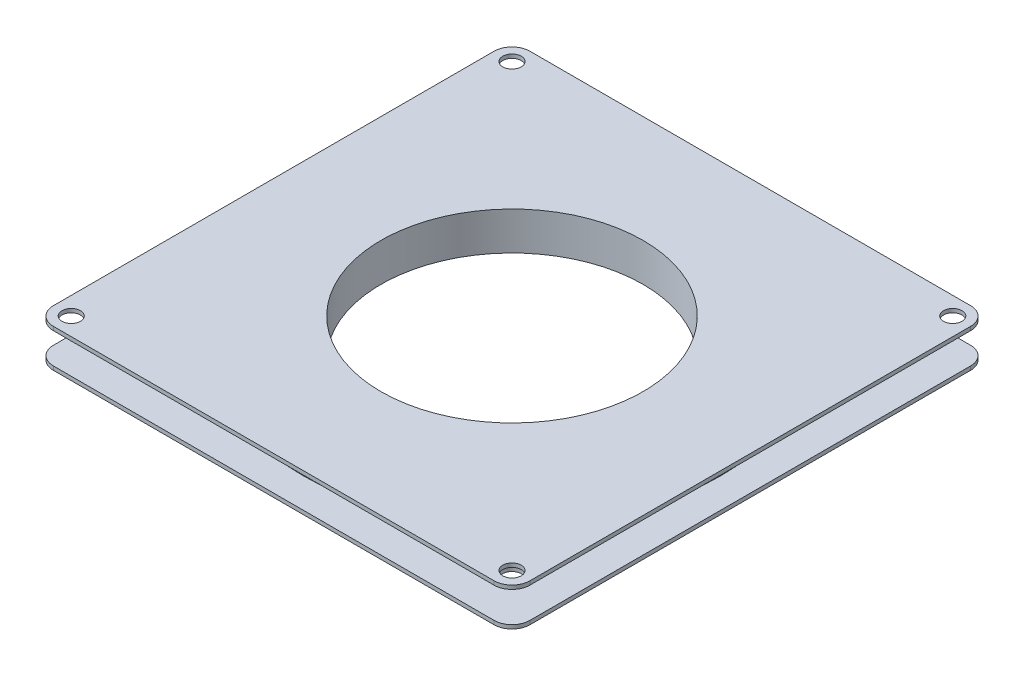
SolidWorks part; units mm, degrees
ref_plane "Front Plane" through (0, 0, 0) normal (0, 0, 1) x (1, 0, 0)
ref_plane "Top Plane" through (0, 0, 0) normal (0, 1, 0) x (1, 0, 0)
ref_plane "Right Plane" through (0, 0, 0) normal (1, 0, 0) x (0, 0, -1)
sketch "Lower_Deck" plane through (0, 0, 0) normal (0, 1, 0) x (1, 0, 0)
  line L1 (0, 0) -> (101.6, 0)
  line L2 (0, 0) -> (0, 101.6)
  line L3 (0, 101.6) -> (101.6, 101.6)
  line L4 (101.6, 0) -> (101.6, 101.6)
  circle A0 centre (10.3505, 10.3505) radius 1.9685
  circle A1 centre (10.3505, 91.2495) radius 1.9685
  circle A2 centre (91.2495, 10.3505) radius 1.9685
  circle A3 centre (91.2495, 91.2495) radius 1.9685
  circle A4 centre (50.8, 50.8) radius 27.94
  point P17 (-50.8076, 117.2435)
  dimension "D1" = 10.3505
  dimension "D7" = 50.8
  dimension "D9" = 55.88
  dimension "D10" = 3.937
  dimension "D2" = 91.2495
  dimension "D3" = 101.6
  dimension "D4" = 101.6
  dimension "D5" = 10.3505
  dimension "D6" = 91.2495
  dimension "D8" = 50.8
extrude "Boss-Extrude1" add sketch "Lower_Deck" along normal blind 0.8128
fillet "Fillet1" radius 3.81 4 edges at (101.6, 0.4064, 0) (101.6, 0.4064, -101.6) (0, 0.4064, -101.6) (0, 0.4064, 0)
ref_plane "Plane1" through (0, 7.3152, 0) normal (0, 1, 0) x (1, 0, 0)
sketch "Sketch2" plane through (0, 7.3152, 0) normal (0, 1, 0) x (1, 0, 0)
  line L1 (0, 0) -> (101.6, 0)
  line L2 (0, 0) -> (0, 101.6)
  line L3 (0, 101.6) -> (101.6, 101.6)
  line L4 (101.6, 0) -> (101.6, 101.6)
  circle A0 centre (50.8, 50.8) radius 27.94
  circle A1 centre (3.81, 3.81) radius 1.9685
  circle A2 centre (3.81, 97.79) radius 1.9685
  circle A3 centre (97.79, 97.79) radius 1.9685
  circle A4 centre (97.79, 3.81) radius 1.9685
extrude "Boss-Extrude2" add sketch "Sketch2" along normal blind 0.8128 separate body
fillet "Fillet3" radius 3.81 4 edges at (101.6, 7.7216, 0) (101.6, 7.7216, -101.6) (0, 7.7216, -101.6) (0, 7.7216, 0)
sketch "Sketch3" plane through (0, 0.8128, 0) normal (0, 1, 0) x (1, 0, 0)
  circle A0 centre (50.8, 50.8) radius 44.45
  circle A1 centre (50.8, 50.8) radius 27.94
extrude "Boss-Extrude3" add sketch "Sketch3" along normal up to next
